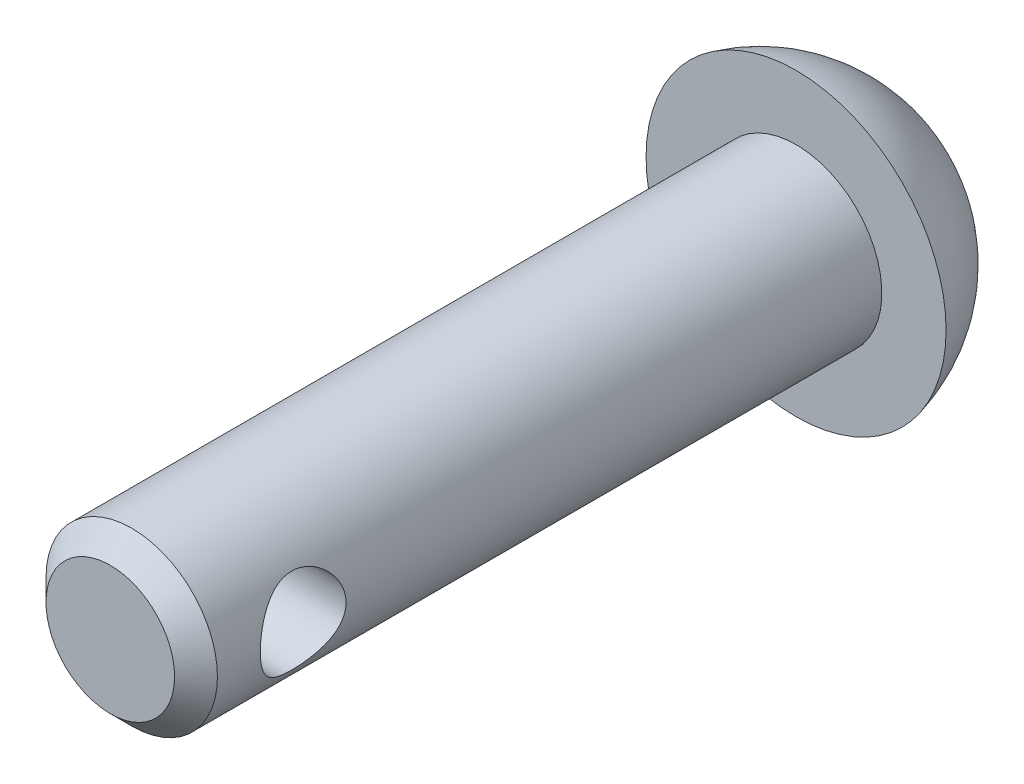
SolidWorks part; units mm, degrees
material "AISI 1035 Steel (SS)"
ref_plane "Front Plane" through (0, 0, 0) normal (0, 0, 1) x (1, 0, 0)
ref_plane "Top Plane" through (0, 0, 0) normal (0, 1, 0) x (1, 0, 0)
ref_plane "Right Plane" through (0, 0, 0) normal (1, 0, 0) x (0, 0, -1)
sketch "Sketch1" plane through (0, 0, 0) normal (0, 0, 1) x (1, 0, 0)
  circle A0 centre (0, 0) radius 2
  dimension "D1" = 4
extrude "Boss-Extrude1" add sketch "Sketch1" along normal mid plane 16
sketch "Sketch2" plane through (0, 0, 0) normal (1, 0, 0) x (0, 0, -1)
  line L0 (5.8311, 0) -> (10.7574, 0) construction
  line L1 (8, -2) -> (8, 2) construction
  line L2 (8, 3.5) -> (8, 0)
  line L3 (8, 0) -> (10.7574, 0)
  arc A0 (8, 3.5) -> (10.7574, 0) centre (7.1574, 0) cw
  dimension "D2" = 3.6
  dimension "D1" = 3.5
revolve "Revolve1" add sketch "Sketch2" angle 360 about L0
sketch "Sketch3" plane through (0, 0, 0) normal (1, 0, 0) x (0, 0, -1)
  line L0 (8, 3.5) -> (8, -3.5) construction
  circle A0 centre (-5.5, 0) radius 1
  dimension "D1" = 2
  dimension "D2" = 13.5
extrude "Cut-Extrude2" cut sketch "Sketch3" against normal through all both and the other way through all contours A0
chamfer "Chamfer1" distance 0.5 angle 45 1 edges at (2, 0, 8)
